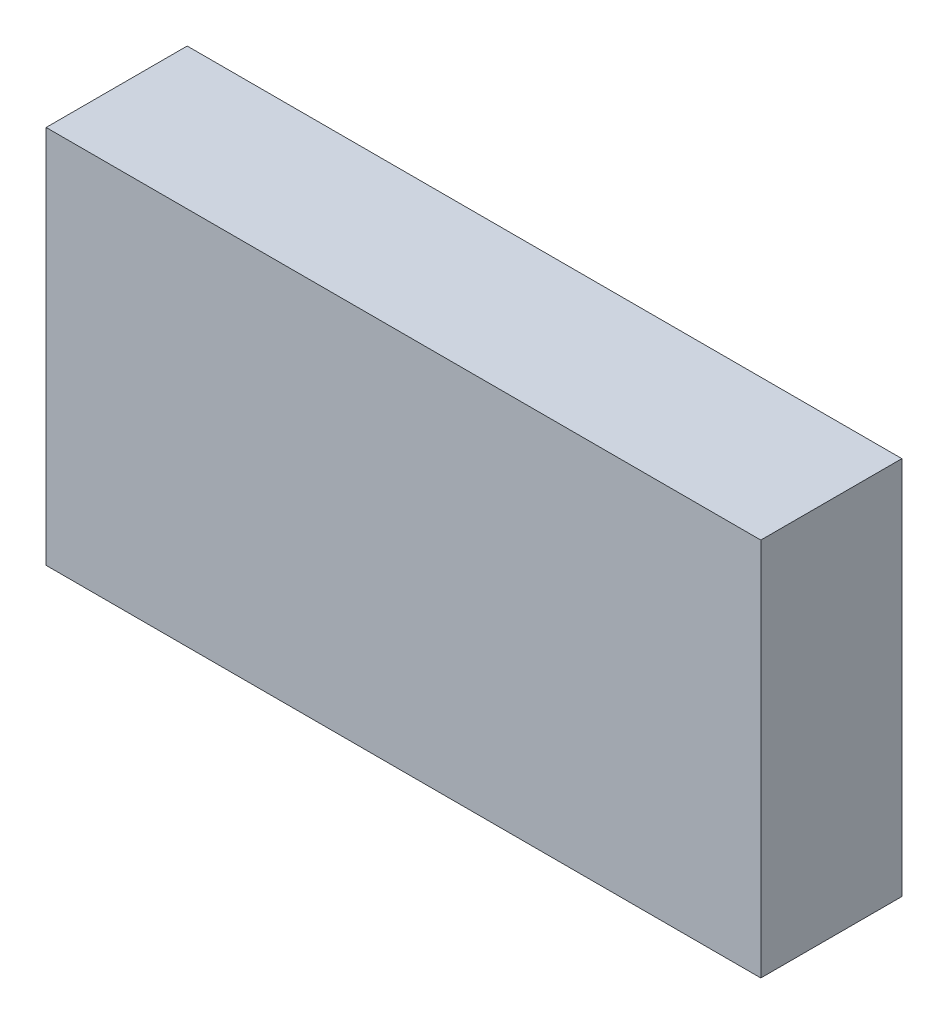
SolidWorks part; units mm, degrees
ref_plane "Front Plane" through (0, 0, 0) normal (0, 0, 1) x (1, 0, 0)
ref_plane "Top Plane" through (0, 0, 0) normal (0, 1, 0) x (1, 0, 0)
ref_plane "Right Plane" through (0, 0, 0) normal (1, 0, 0) x (0, 0, -1)
sketch "Sketch1" plane through (0, 0, 0) normal (0, 0, 1) x (1, 0, 0)
  line L1 (-24.3788, 13.1517) -> (26.2867, 13.1517)
  line L2 (-24.3788, 13.1517) -> (-24.3788, -13.7349)
  line L3 (-24.3788, -13.7349) -> (26.2867, -13.7349)
  line L4 (26.2867, 13.1517) -> (26.2867, -13.7349)
sketch3d "3DSketch1" plane through (0, 0, 0) normal (0, 0, 1) x (1, 0, 0)
extrude "Boss-Extrude1" add sketch "Sketch1" along normal blind 10 contours L1 L4 L3 L2
